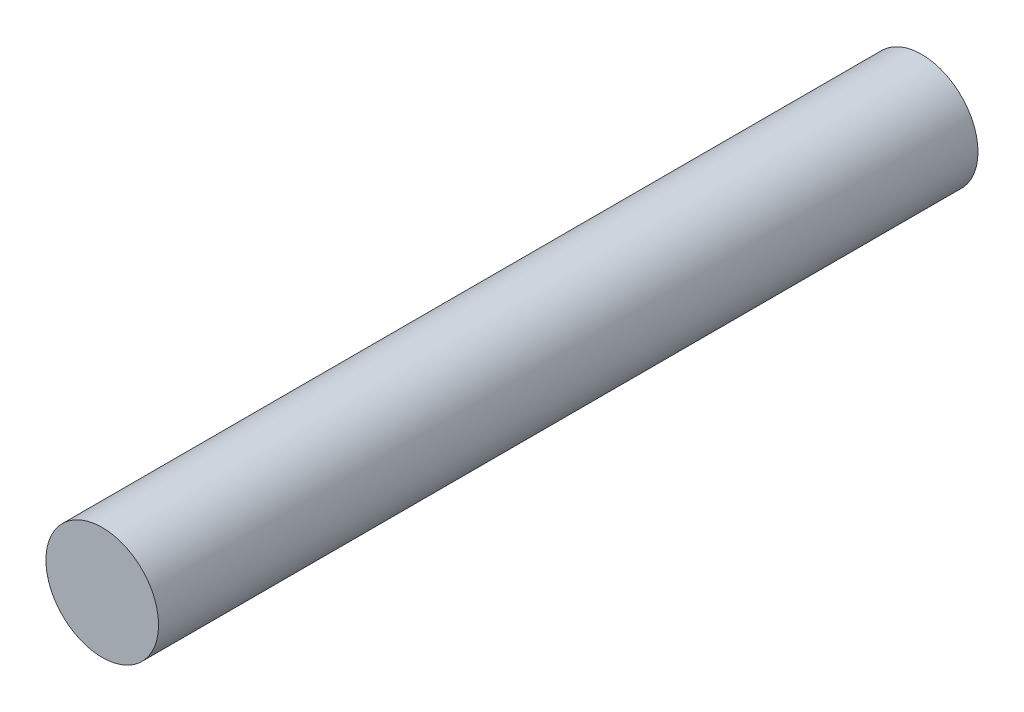
SolidWorks part; units mm, degrees
ref_plane "Front Plane" through (0, 0, 0) normal (0, 0, 1) x (1, 0, 0)
ref_plane "Top Plane" through (0, 0, 0) normal (0, 1, 0) x (1, 0, 0)
ref_plane "Right Plane" through (0, 0, 0) normal (1, 0, 0) x (0, 0, -1)
sketch "Sketch1" plane through (0, 0, 0) normal (0, 0, 1) x (1, 0, 0)
  circle A0 centre (0, 0) radius 10.9995
  dimension "D1" = 21.999
extrude "Boss-Extrude1" add sketch "Sketch1" along normal blind 160
